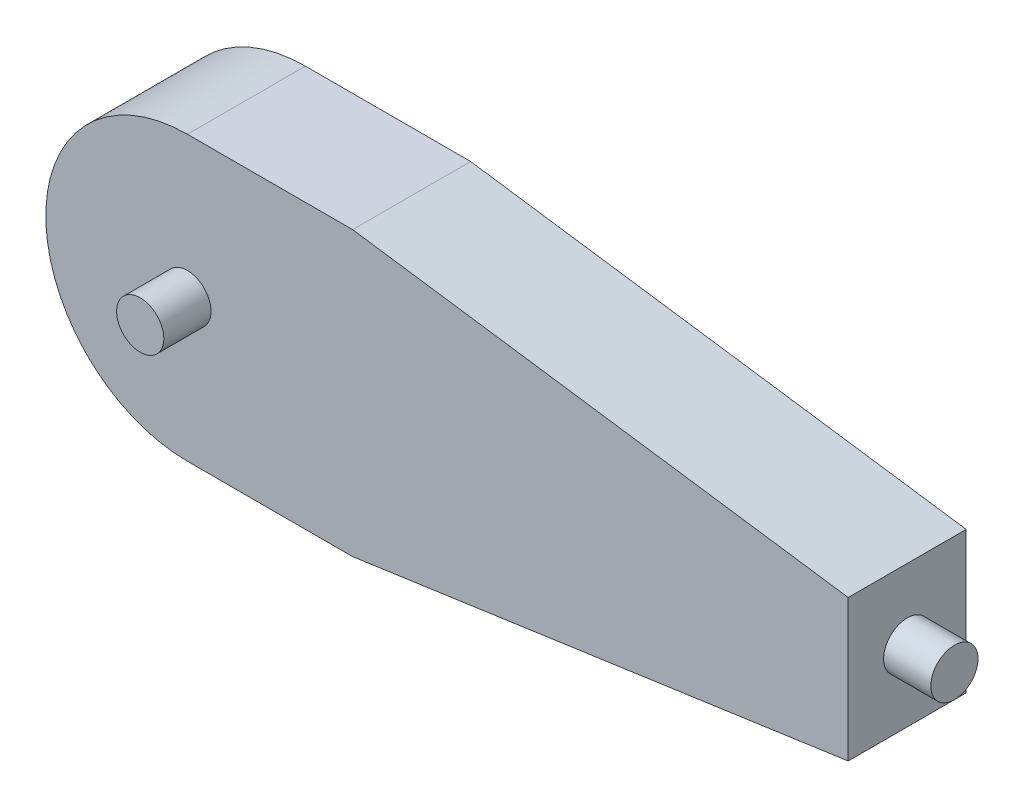
SolidWorks part; units mm, degrees
ref_plane "Front Plane" through (0, 0, 0) normal (0, 0, 1) x (1, 0, 0)
ref_plane "Top Plane" through (0, 0, 0) normal (0, 1, 0) x (1, 0, 0)
ref_plane "Right Plane" through (0, 0, 0) normal (1, 0, 0) x (0, 0, -1)
sketch "Sketch1" plane through (0, 0, 0) normal (0, 0, 1) x (1, 0, 0)
  line L0 (0, 0) -> (280, 0) construction
  line L1 (0, 60) -> (70, 60)
  line L2 (0, -60) -> (70, -60)
  line L3 (70, 60) -> (280, 30)
  line L4 (70, -60) -> (280, -30)
  line L5 (280, 30) -> (280, -30)
  arc A0 (0, 60) -> (0, -60) centre (0, 0) ccw
  dimension "D1" = 60
  dimension "D2" = 60
  dimension "D3" = 70
  dimension "D4" = 280
extrude "Boss-Extrude1" add sketch "Sketch1" along normal blind 50
sketch "Sketch2" plane through (0, 0, 50) normal (0, 0, 1) x (1, 0, 0)
  circle A0 centre (0, 0) radius 10
  dimension "D1" = 20
sketch "Sketch3" plane through (280, 0, 0) normal (1, 0, 0) x (0, 0, -1)
  line L0 (0, -30) -> (0, 30) construction
  line L1 (-50, 30) -> (0, 30) construction
  circle A0 centre (-25, 0) radius 10
  point P4 (0, 0)
  point P8 (-25, 30)
  dimension "D1" = 20
ref_plane "Plane1" through (0, 0, 25) normal (0, 0, 1) x (1, 0, 0)
sketch "Sketch4" plane through (0, 0, 25) normal (0, 0, 1) x (1, 0, 0)
  line L0 (0, 0) -> (103.7934, 0) construction
  line L1 (0, 0) -> (0, -103.7934) construction
  line L2 (0, 0) -> (148.9922, 0) construction
  text T0 "X3" font "Century Gothic" height 20
  text T1 "Z3" font "Century Gothic" height 20
  point P6 (0, 0)
  point P7 (0, 82.1313)
  point P8 (0, 133.8193)
  point P9 (0, -117.2405)
  point P10 (0, -128.3562)
  point P11 (0, -147.3375)
  point P12 (103.7934, 0)
ref_plane "Plane2" through (0, 0, 0) normal (0, 1, 0) x (1, 0, 0)
sketch "Sketch5" plane through (0, 0, 0) normal (0, 1, 0) x (1, 0, 0)
  line L0 (0, -25) -> (0, 78.5824) construction
  line L1 (0, -25) -> (0, 123.9922) construction
  line L2 (0, -25) -> (103.7934, -25) construction
  text T0 "Y3" font "Century Gothic" height 20
  point P0 (0, 78.5824)
extrude "Boss-Extrude2" add sketch "Sketch2" along normal blind 20
extrude "Boss-Extrude3" add sketch "Sketch3" along normal blind 20
